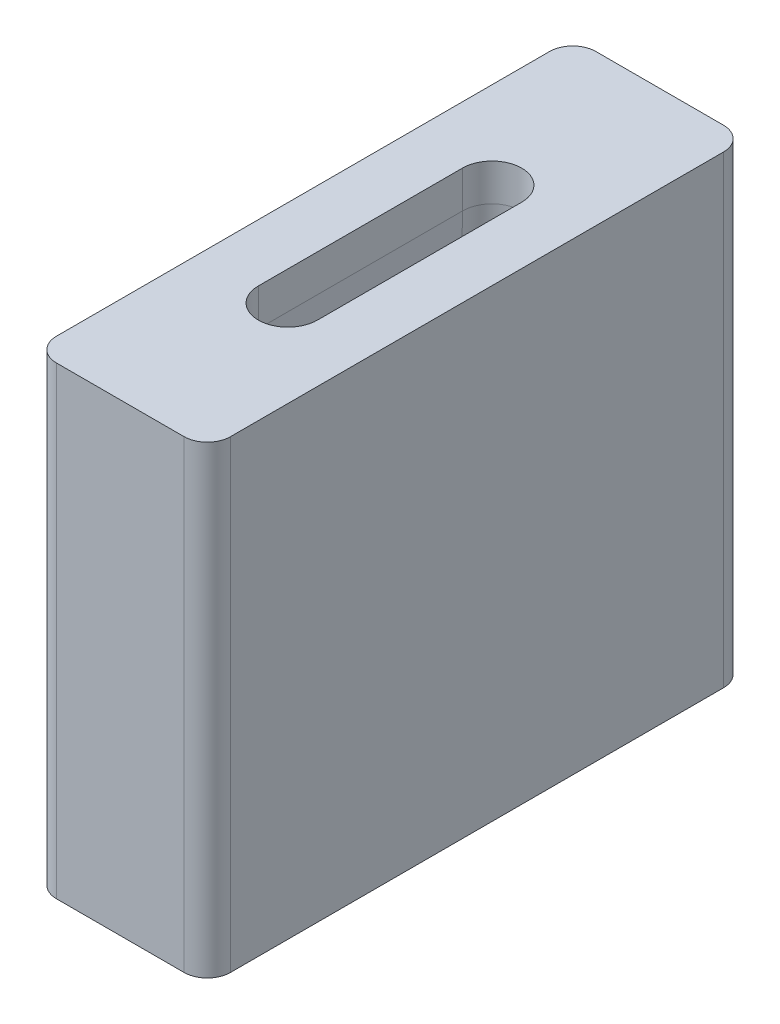
SolidWorks part; units mm, degrees
material "K110"
ref_plane "Front Plane" through (0, 0, 0) normal (0, 0, 1) x (1, 0, 0)
ref_plane "Top Plane" through (0, 0, 0) normal (0, 1, 0) x (1, 0, 0)
ref_plane "Right Plane" through (0, 0, 0) normal (1, 0, 0) x (0, 0, -1)
sketch "Sketch1" plane through (0, 0, 0) normal (0, 1, 0) x (1, 0, 0)
  line L3 (0, -3.5) -> (0, 3.5) construction
  line L4 (-2.62, -3.5) -> (-2.62, 3.5) construction
  line L5 (2.62, -3.5) -> (2.62, 3.5) construction
  line L6 (-5.5, -23.25) -> (5.5, -23.25)
  line L7 (-7.5, -21.25) -> (-7.5, 21.25)
  line L8 (-5.5, 23.25) -> (5.5, 23.25)
  line L9 (7.5, -21.25) -> (7.5, 21.25)
  line L10 (-7.5, -23.25) -> (7.5, 23.25) construction
  line L11 (-7.5, 23.25) -> (7.5, -23.25) construction
  arc A2 (-2.62, -3.5) -> (2.62, -3.5) centre (0, -3.5) ccw construction
  arc A3 (2.62, 3.5) -> (-2.62, 3.5) centre (0, 3.5) ccw construction
  arc A4 (-5.5, -23.25) -> (-7.5, -21.25) centre (-5.5, -21.25) cw
  arc A5 (5.5, -23.25) -> (7.5, -21.25) centre (5.5, -21.25) ccw
  arc A6 (5.5, 23.25) -> (7.5, 21.25) centre (5.5, 21.25) cw
  arc A7 (-7.5, 21.25) -> (-5.5, 23.25) centre (-5.5, 21.25) cw
  point P0 (0, 0)
  point P10 (0, 0)
  dimension "D1" = 7
  dimension "D3" = 2.62
  dimension "D5" = 2
  dimension "D2" = 46.5
  dimension "D4" = 15
extrude "Boss-Extrude1" add sketch "Sketch1" against normal blind 40
sketch "Sketch5" plane through (0, 0, 0) normal (0, 1, 0) x (1, 0, 0)
  line L0 (0, -8.8) -> (0, 8.8) construction
  line L1 (-2.55, -8.8) -> (-2.55, 8.8)
  line L2 (2.55, -8.8) -> (2.55, 8.8)
  arc A0 (-2.55, -8.8) -> (2.55, -8.8) centre (0, -8.8) ccw
  arc A1 (2.55, 8.8) -> (-2.55, 8.8) centre (0, 8.8) ccw
  point P4 (0, 0)
  dimension "D1" = 17.6
  dimension "D2" = 5.1
extrude "Cut-Extrude2" cut sketch "Sketch5" against normal up to next
sketch "Sketch7" plane through (0, 0, 0) normal (0, 0, 1) x (1, 0, 0)
  line L0 (2.55, -3.2) -> (3.1923, -40)
  line L1 (2.55, -40) -> (2.55, 0) construction
  line L2 (-5.5, -40) -> (5.5, -40) construction
  line L3 (3.1923, -40) -> (2.55, -40)
  line L4 (2.55, -40) -> (2.55, -3.2)
  line L5 (7.5, 0) -> (5.5, 0) construction
  dimension "D1" = 3.2
  dimension "D2" = 1
sketch "Sketch8" plane through (0, 0, 0) normal (0, 1, 0) x (1, 0, 0)
  line L0 (-2.55, 8.8) -> (-2.55, -8.8) construction
  line L1 (2.55, -8.8) -> (2.55, 8.8) construction
  line L2 (-2.55, 8.8) -> (-2.55, -8.8)
  line L3 (2.55, -8.8) -> (2.55, 8.8)
  arc A0 (2.55, 8.8) -> (-2.55, 8.8) centre (0, 8.8) ccw construction
  arc A1 (-2.55, -8.8) -> (2.55, -8.8) centre (0, -8.8) ccw construction
  arc A2 (2.55, 8.8) -> (-2.55, 8.8) centre (0, 8.8) ccw
  arc A3 (-2.55, -8.8) -> (2.55, -8.8) centre (0, -8.8) ccw
sweep "Cut-Sweep1" cut profiles "Sketch7" path "Sketch8"
hole_wizard "M6 Tapped Hole1" positions "Sketch11" profile "Sketch10" tap size "M6" standard "ISO"
sketch "Sketch11" plane through (0, -40, 0) normal (0, -1, 0) x (-1, 0, 0)
  line L0 (-5.5, 23.25) -> (5.5, 23.25) construction
  line L5 (5.5, -23.25) -> (-5.5, -23.25) construction
  line L6 (0, 23.25) -> (0, -23.25) construction
  point P0 (0, 19.25)
  point P2 (0, -19.25)
  dimension "D1" = 4
  dimension "D4" = 4
sketch "Sketch10" plane through (0, -40, -19.25) normal (1, 0, 0) x (0, 0, -1)
  line L0 (0, 0) -> (0, 18.5022)
  line L1 (0, 18.5022) -> (2.5, 17)
  line L2 (2.5, 17) -> (2.5, 0.525)
  line L3 (2.5, 0.525) -> (3.025, 0)
  line L5 (3.025, 0) -> (0, 0)
  line L6 (-2.5, 0.525) -> (-3.025, 0) construction
  line L10 (0, 18.5022) -> (-2.5, 17) construction
  line L11 (0, -6.35) -> (0, 107.95) construction
  dimension "Tap Drill Dia." = 5
  dimension "Tap Drill Depth" = 17
  dimension "Near C'Sink Dia." = 6.05
  dimension "Near C'Sink Angle" = 90
  dimension "Drill Angle" = 118
cosmetic thread "Hole Thread1"
cosmetic thread "Hole Thread2"
